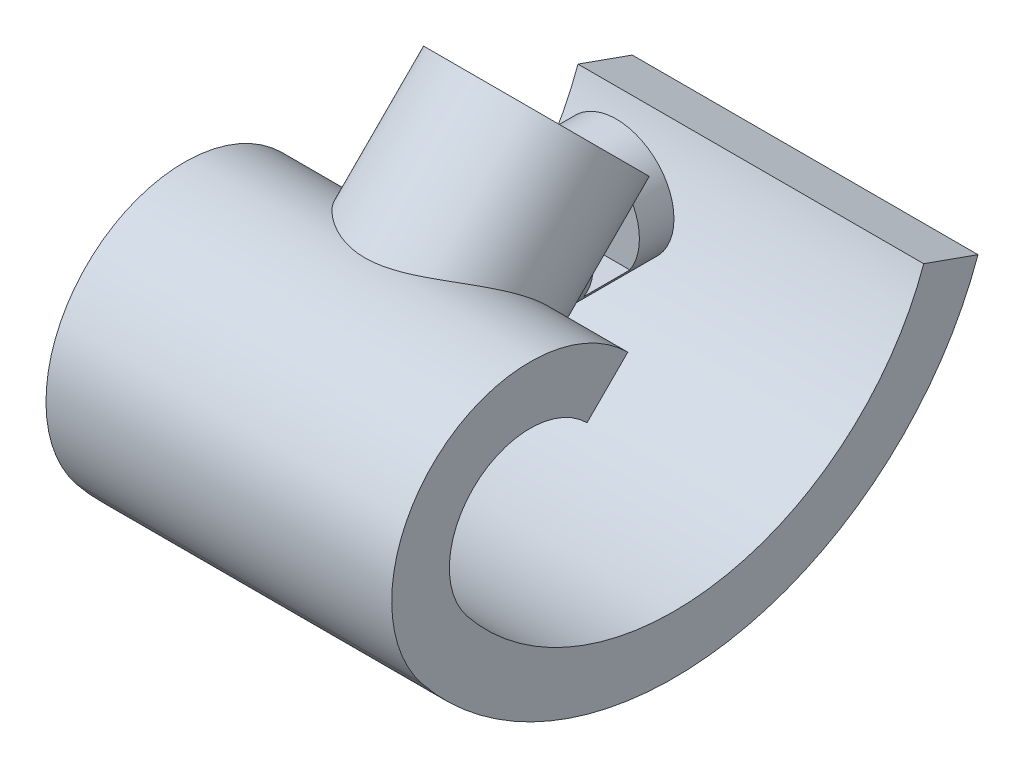
SolidWorks part; units mm, degrees
ref_plane "Спереди" through (0, 0, 0) normal (0, 0, 1) x (1, 0, 0)
ref_plane "Сверху" through (0, 0, 0) normal (0, 1, 0) x (1, 0, 0)
ref_plane "Справа" through (0, 0, 0) normal (1, 0, 0) x (0, 0, -1)
sketch "Sketch1" plane through (0, 0, 0) normal (1, 0, 0) x (0, 0, -1)
  line L0 (-4.0047, 8.4853) -> (-12.49, 0) construction
  line L1 (-12.49, 0) -> (-12.49, 19.5798) construction
  arc A0 (-21.8575, -7.5) -> (26.3823, 0.6205) centre (0, 10) ccw
  arc A1 (-21.8575, -7.5) -> (-4.0047, 8.4853) centre (-12.49, 0) cw
  dimension "D1" = 28
  dimension "D3" = 12
  dimension "D2" = 10
  dimension "D4" = 45
extrude "Extrude-Thin1" add sketch "Sketch1" along normal mid plane 30 thin thin type one direction wall 5
sketch "Sketch2" plane through (0, 0, 0) normal (1, 0, 0) x (0, 0, -1)
  line L0 (-12.49, 0) -> (-4.0047, 8.4853) construction
  line L1 (-4.0047, 8.4853) -> (-12.0252, 16.5058) construction
ref_plane "Plane1" through (0, 2.2403, -2.2403) normal (0, 0.7071, -0.7071) x (1, 0, 0)
sketch "Sketch3" plane through (0, 2.2403, -2.2403) normal (0, 0.7071, -0.7071) x (1, 0, 0)
  line L0 (15, -8.8318) -> (-15, -8.8318) construction
  circle A0 centre (0, -8.8318) radius 4
  circle A1 centre (0, -8.8318) radius 8
  dimension "D1" = 8
  dimension "D2" = 4
extrude "Boss-Extrude1" add sketch "Sketch3" along normal blind 10 and the other way blind 5
sketch "Sketch5" plane through (0, 0, 0) normal (0, 0, 1) x (1, 0, 0)
  circle A0 centre (0, 6.5) radius 5
  dimension "D1" = 10
  dimension "D2" = 6.5
extrude "Boss-Extrude2" add sketch "Sketch5" against normal blind 10
sketch "Sketch6" plane through (0, 0, -10) normal (0, 0, -1) x (-1, 0, 0)
  circle A0 centre (0, 6.5) radius 1.5
  dimension "D1" = 3
extrude "Cut-Extrude2" cut sketch "Sketch6" against normal blind 14
sketch "Sketch4" plane through (0, 9.3114, -9.3114) normal (0, 0.7071, -0.7071) x (1, 0, 0)
  circle A0 centre (0, -8.8318) radius 4
  circle A1 centre (0, -8.8318) radius 4 construction
extrude "Cut-Extrude1" cut sketch "Sketch4" against normal blind 20
ref_plane "Plane2" through (0, 0, -7) normal (0, 0, -1) x (-1, 0, 0)
sketch "Sketch7" plane through (0, 0, -7) normal (0, 0, -1) x (-1, 0, 0)
  line L0 (-1.5877, 9.25) -> (-18.5606, 9.25)
  line L1 (3.1754, 6.5) -> (1.5877, 9.25)
  line L2 (1.5877, 9.25) -> (-1.5877, 9.25)
  line L3 (-1.5877, 9.25) -> (-3.1754, 6.5)
  line L4 (-3.1754, 6.5) -> (-1.5877, 3.75)
  line L5 (-1.5877, 3.75) -> (1.5877, 3.75)
  line L6 (1.5877, 3.75) -> (3.1754, 6.5)
  line L7 (-18.5606, 9.25) -> (-18.5606, 3.75)
  line L8 (-18.5606, 3.75) -> (-1.5877, 3.75)
  circle A0 centre (0, 6.5) radius 2.75 construction
  dimension "D1" = 5.5
extrude "Cut-Extrude3" cut sketch "Sketch7" against normal blind 3 contours L5 L6 L1 L2 L3 L4 | L7 L8 L4 L3 L0
chamfer "Chamfer1" distance 1 angle 45 1 edges at (4.9131, 5.5719, -4)
